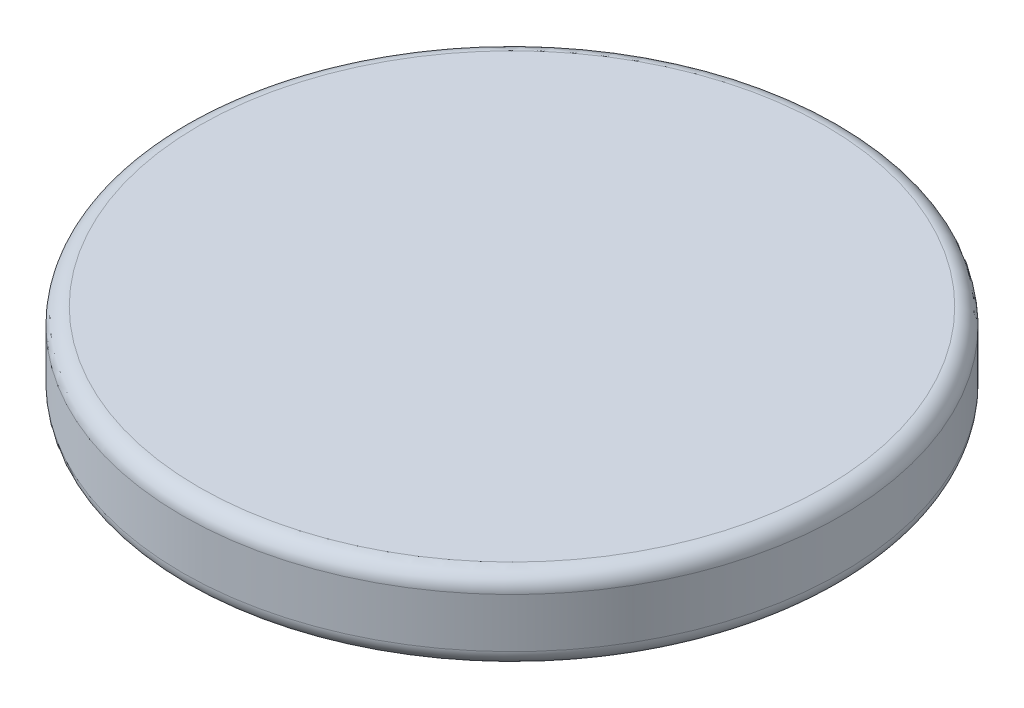
SolidWorks part; units mm, degrees
ref_plane "Front" through (0, 0, 0) normal (0, 0, 1) x (1, 0, 0)
ref_plane "Top" through (0, 0, 0) normal (0, 1, 0) x (1, 0, 0)
ref_plane "Right" through (0, 0, 0) normal (1, 0, 0) x (0, 0, -1)
sketch "Эскиз1" plane through (0, 0, 0) normal (0, 1, 0) x (1, 0, 0)
  circle A0 centre (0, 0) radius 4
  dimension "D1" = 8
extrude "Бобышка-Вытянуть1" add sketch "Эскиз1" along normal blind 1
fillet "Скругление1" radius 0.2 2 edges at (0, 0, 4) (0, 1, 4)
